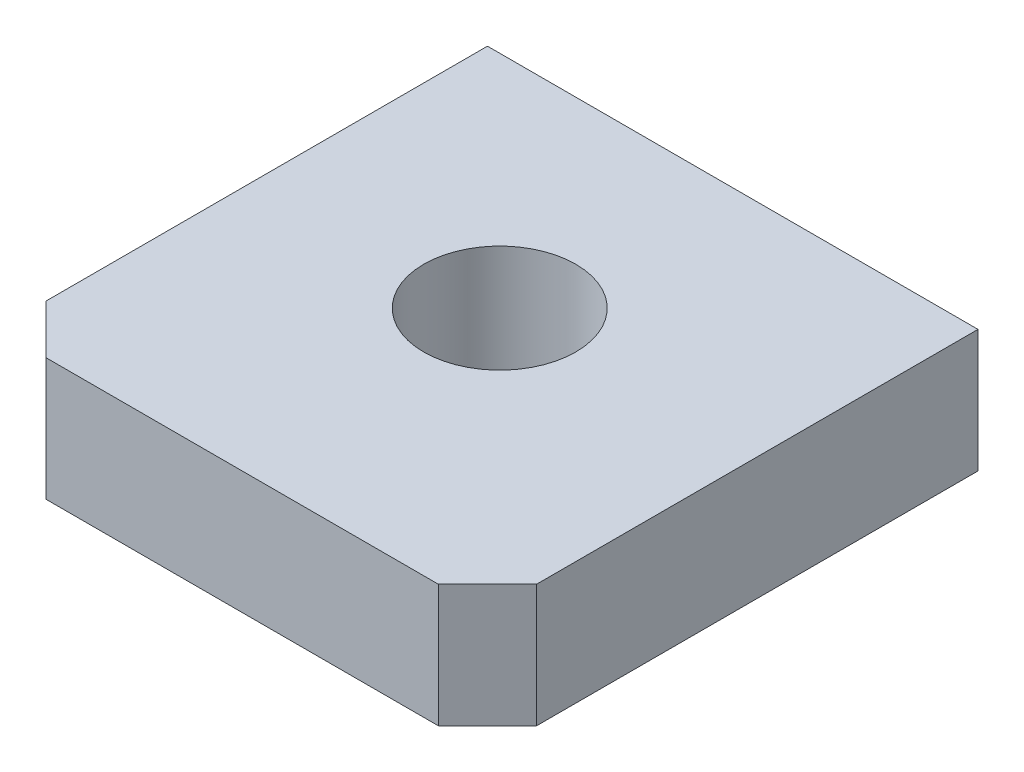
SolidWorks part; units mm, degrees
ref_plane "정면" through (0, 0, 0) normal (0, 0, 1) x (1, 0, 0)
ref_plane "윗면" through (0, 0, 0) normal (0, 1, 0) x (1, 0, 0)
ref_plane "우측면" through (0, 0, 0) normal (1, 0, 0) x (0, 0, -1)
sketch "스케치1" plane through (0, 0, 0) normal (0, 1, 0) x (1, 0, 0)
  line L1 (0, 0) -> (20, 0)
  line L2 (0, 0) -> (0, 20)
  line L3 (0, 20) -> (20, 20)
  line L4 (20, 0) -> (20, 20)
  dimension "D1" = 20
  dimension "D2" = 20
extrude "보스-돌출1" add sketch "스케치1" along normal blind 5
sketch "스케치2" plane through (0, 5, 0) normal (0, 1, 0) x (1, 0, 0)
  line L0 (20, 0) -> (20, 20) construction
  line L1 (0, 0) -> (20, 0) construction
  circle A0 centre (9.5, 11) radius 3.1
  dimension "D2" = 6.2
  dimension "D1" = 10.5
  dimension "D3" = 11
extrude "컷-돌출1" cut sketch "스케치2" against normal blind 5
chamfer "모따기1" distance 2 angle 45 2 edges at (20, 2.5, 0) (0, 2.5, 0)
